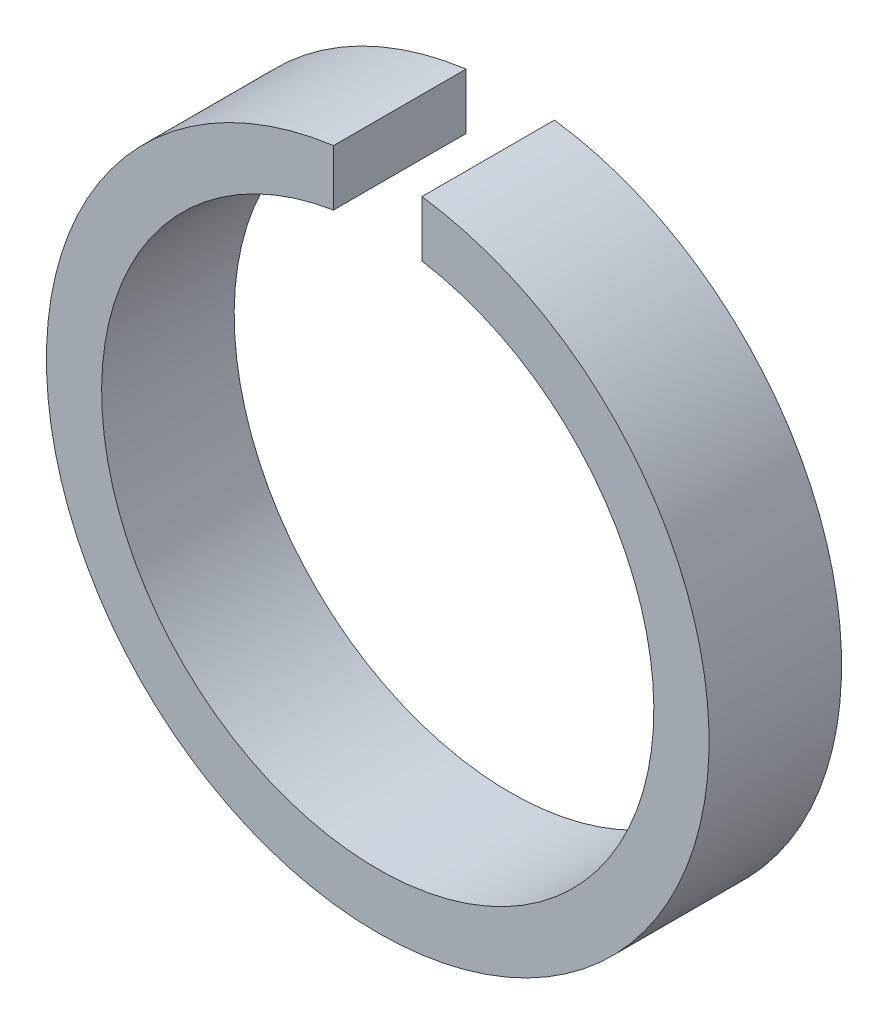
SolidWorks part; units mm, degrees
ref_plane "前视基准面" through (0, 0, 0) normal (0, 0, 1) x (1, 0, 0)
ref_plane "上视基准面" through (0, 0, 0) normal (0, 1, 0) x (1, 0, 0)
ref_plane "右视基准面" through (0, 0, 0) normal (1, 0, 0) x (0, 0, -1)
sketch "草图1" plane through (0, 0, 0) normal (0, 0, 1) x (1, 0, 0)
  circle A0 centre (0, 0) radius 6.25
  circle A1 centre (0, 0) radius 7.5
  dimension "D1" = 12.5
  dimension "D2" = 15
extrude "凸台-拉伸1" add sketch "草图1" along normal blind 3
sketch "草图2" plane through (0, 0, 3) normal (0, 0, 1) x (1, 0, 0)
  line L0 (0, -1000) -> (0, 49000) construction
  line L2 (-1, 0) -> (1, 0)
  line L3 (-1, 0) -> (-1, 7.5)
  line L4 (-1, 7.5) -> (1, 7.5)
  line L5 (1, 0) -> (1, 7.5)
  circle A0 centre (0, 0) radius 7.5 construction
  dimension "D1" = 2
extrude "切除-拉伸1" cut sketch "草图2" against normal through all
